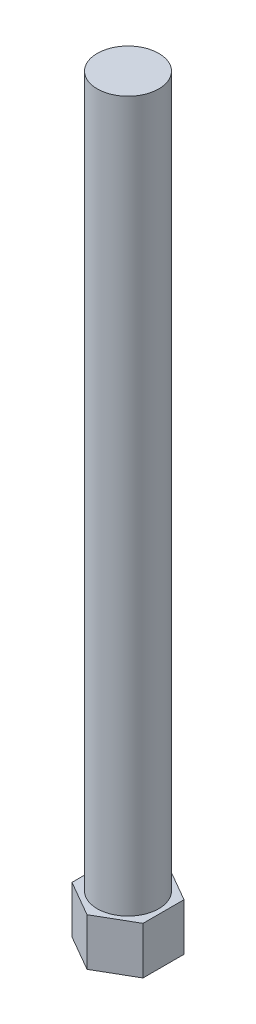
SolidWorks part; units mm, degrees
ref_plane "Front Plane" through (0, 0, 0) normal (0, 0, 1) x (1, 0, 0)
ref_plane "Top Plane" through (0, 0, 0) normal (0, 1, 0) x (1, 0, 0)
ref_plane "Right Plane" through (0, 0, 0) normal (1, 0, 0) x (0, 0, -1)
sketch "Sketch1" plane through (0, 0, 0) normal (0, 1, 0) x (1, 0, 0)
  line L1 (0.15, -0.0866) -> (0.15, 0.0866)
  line L2 (0.15, 0.0866) -> (0, 0.1732)
  line L3 (0, 0.1732) -> (-0.15, 0.0866)
  line L4 (-0.15, 0.0866) -> (-0.15, -0.0866)
  line L5 (-0.15, -0.0866) -> (0, -0.1732)
  line L6 (0, -0.1732) -> (0.15, -0.0866)
  circle A0 centre (0, 0) radius 0.15 construction
  dimension "D1" = 0.3
extrude "Boss-Extrude1" add sketch "Sketch1" along normal blind 0.2
sketch "Sketch2" plane through (0, 0.2, 0) normal (0, 1, 0) x (1, 0, 0)
  circle A0 centre (0, 0) radius 0.13
  dimension "D1" = 0.26
extrude "Boss-Extrude2" add sketch "Sketch2" along normal blind 3
